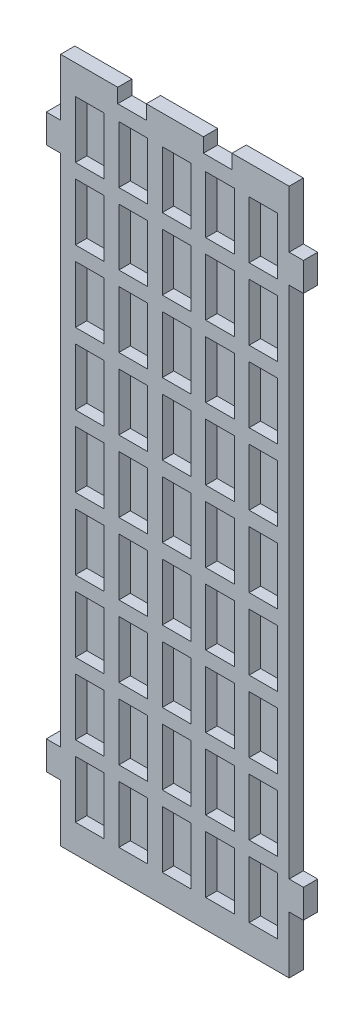
SolidWorks part; units mm, degrees
ref_plane "Front Plane" through (0, 0, 0) normal (0, 0, 1) x (1, 0, 0)
ref_plane "Top Plane" through (0, 0, 0) normal (0, 1, 0) x (1, 0, 0)
ref_plane "Right Plane" through (0, 0, 0) normal (1, 0, 0) x (0, 0, -1)
sketch "Sketch1" plane through (0, 0, 0) normal (0, 0, 1) x (1, 0, 0)
  line L0 (19.05, 0) -> (31.75, 0)
  line L1 (0, 0) -> (12.7, 0)
  line L2 (0, 0) -> (0, -12.7)
  line L3 (0, -152.4) -> (12.7, -152.4)
  line L4 (50.8, -19.05) -> (50.8, -133.35)
  line L5 (38.1, 0) -> (50.8, 0)
  line L6 (12.7, 0) -> (12.7, -3.175)
  line L7 (12.7, -3.175) -> (19.05, -3.175)
  line L8 (19.05, 0) -> (19.05, -3.175)
  line L9 (0, -19.05) -> (0, -133.35)
  line L10 (31.75, 0) -> (31.75, -3.175)
  line L11 (31.75, -3.175) -> (38.1, -3.175)
  line L12 (38.1, 0) -> (38.1, -3.175)
  line L13 (50.8, -12.7) -> (53.975, -12.7)
  line L14 (50.8, -139.7) -> (50.8, -152.4)
  line L15 (50.8, -19.05) -> (53.975, -19.05)
  line L16 (53.975, -12.7) -> (53.975, -19.05)
  line L17 (50.8, -133.35) -> (53.975, -133.35)
  line L18 (38.1, -152.4) -> (50.8, -152.4)
  line L19 (50.8, -139.7) -> (53.975, -139.7)
  line L20 (53.975, -133.35) -> (53.975, -139.7)
  line L21 (12.7, -152.4) -> (38.1, -152.4)
  line L25 (0, -139.7) -> (0, -152.4)
  line L29 (0, -139.7) -> (-3.175, -139.7)
  line L31 (0, -133.35) -> (-3.175, -133.35)
  line L32 (-3.175, -139.7) -> (-3.175, -133.35)
  line L33 (0, -19.05) -> (-3.175, -19.05)
  line L34 (50.8, 0) -> (50.8, -12.7)
  line L35 (0, -12.7) -> (-3.175, -12.7)
  line L36 (-3.175, -19.05) -> (-3.175, -12.7)
  dimension "D3" = 12.7
  dimension "D4" = 6.35
  dimension "D5" = 3.175
  dimension "D6" = 6.35
  dimension "D7" = 3.175
  dimension "D8" = 12.7
  dimension "D9" = 152.4
  dimension "D10" = 6.35
  dimension "D11" = 3.175
  dimension "D12" = 3.175
  dimension "D13" = 6.35
  dimension "D14" = 12.7
  dimension "D15" = 50.8
  dimension "D21" = 3.175
  dimension "D22" = 6.35
  dimension "D23" = 12.7
  dimension "D24" = 12.7
  dimension "D25" = 6.35
  dimension "D26" = 3.175
  dimension "D27" = 3.175
  dimension "D29" = 3.175
  dimension "D30" = 12.7
extrude "Boss-Extrude1" add sketch "Sketch1" along normal blind 3.175
sketch "Sketch2" plane through (0, 0, 3.175) normal (0, 0, 1) x (1, 0, 0)
  line L0 (12.7, -3.175) -> (19.05, -3.175) construction
  line L1 (3.302, -6.477) -> (9.652, -6.477)
  line L2 (3.302, -6.477) -> (3.302, -19.177)
  line L3 (3.302, -19.177) -> (9.652, -19.177)
  line L4 (9.652, -6.477) -> (9.652, -19.177)
  line L5 (3.302, -6.477) -> (9.652, -19.177) construction
  line L6 (3.302, -19.177) -> (9.652, -6.477) construction
  line L7 (0, -19.05) -> (0, -133.35) construction
  point P0 (6.477, -12.827)
  dimension "D1" = 3.302
  dimension "D2" = 3.302
  dimension "D3" = 12.7
  dimension "D4" = 6.35
extrude "Cut-Extrude1" cut sketch "Sketch2" against normal blind 2.54
pattern_linear "LPattern1" count 5 spacing 9.652 along (1, 0, 0) count 9 spacing 15.875 along (0, -1, 0) of "Cut-Extrude1"
